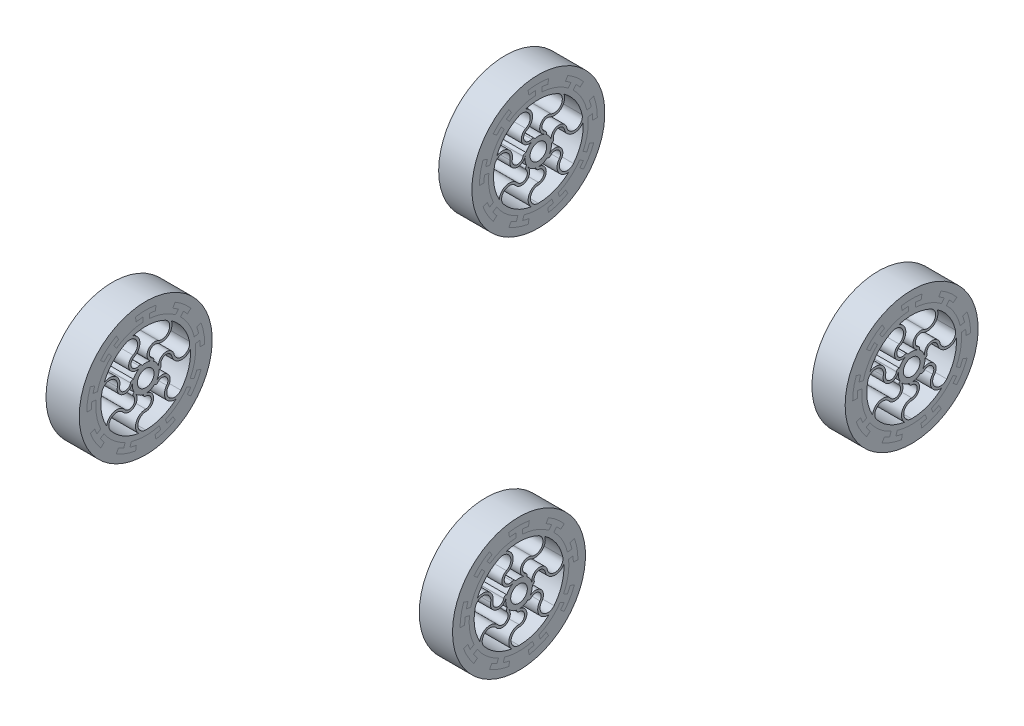
SolidWorks part; units mm, degrees
ref_plane "Front Plane" through (0, 0, 0) normal (0, 0, 1) x (1, 0, 0)
ref_plane "Top Plane" through (0, 0, 0) normal (0, 1, 0) x (1, 0, 0)
ref_plane "Right Plane" through (0, 0, 0) normal (1, 0, 0) x (0, 0, -1)
ref_plane "Plane1" through (64.95, 0, 0) normal (1, 0, 0) x (0, 0, -1)
sketch "Sketch1" plane through (64.95, 0, 0) normal (1, 0, 0) x (0, 0, -1)
  circle A0 centre (0, 0) radius 25.4 construction
  circle A1 centre (0, 0) radius 3.175
  circle A2 centre (0, 0) radius 5.08
  circle A3 centre (0, 0) radius 19.05
  circle A4 centre (0, 0) radius 17.145
  dimension "D1" = 50.8
  dimension "D2" = 38.1
  dimension "D3" = 34.29
  dimension "D4" = 6.35
  dimension "D5" = 10.16
extrude "Boss-Extrude1" add sketch "Sketch1" along normal blind 12.7 contours A3 A4 | A2 A1
sketch "Sketch2" plane through (64.95, 0, 0) normal (1, 0, 0) x (0, 0, -1)
  circle A0 centre (0, 0) radius 5.08
  circle A1 centre (0, 0) radius 17.145
  arc A2 (0, -11.1125) -> (0, -5.08) centre (0, -8.0963) ccw
  arc A3 (0, -11.1125) -> (0, -17.145) centre (0, -14.1288) ccw
  arc A6 (0, -10.2235) -> (-2.7239, -16.9272) centre (0, -14.1288) ccw
  arc A7 (0, -10.2235) -> (0, -5.969) centre (0, -8.0963) ccw
  arc A8 (0, -5.969) -> (-0.8856, -5.0022) centre (0, -5.08) cw
  dimension "D1" = 10.16
  dimension "D2" = 34.29
  dimension "D3" = 0.889
  dimension "D4" = 0
extrude "Boss-Extrude2" add sketch "Sketch2" along normal up to surface (12.7 mm away) contours A8 A7 A6 A1 A3 A2 A0
pattern_circular "CirPattern1" count 7 over 360 about axis through (0, 0, 0) along (1, 0, 0) of "Boss-Extrude2"
sketch "Sketch3" plane through (64.95, 0, 0) normal (1, 0, 0) x (0, 0, -1)
  line L2 (-3.9449, 22.1713) -> (-3.6335, 20.4208)
  line L4 (-1.1102, 20.7118) -> (-1.1102, 19.0176)
  line L6 (3.9449, 22.1713) -> (3.6335, 20.4208)
  line L7 (1.4298, 20.6921) -> (1.4298, 18.9963)
  circle A0 centre (0, 0) radius 19.05 construction
  circle A1 centre (0, 0) radius 19.05
  arc A2 (-3.9449, 22.1713) -> (3.9449, 22.1713) centre (0, 0) cw
  arc A3 (-3.6335, 20.4208) -> (-1.1102, 20.7118) centre (0, 0) cw
  arc A4 (1.4298, 20.6921) -> (3.6335, 20.4208) centre (0, 0) cw
  dimension "D5" = 2.5401
  dimension "D1" = 2.54
  dimension "D2" = 1.778
  dimension "D3" = 2.54
  dimension "D4" = 3.175
extrude "Boss-Extrude3" add sketch "Sketch3" along a picked direction on the side of the normal blind 12.7
pattern_circular "CirPattern2" count 9 over 360 about axis through (0, 0, 0) along (1, 0, 0) of "Boss-Extrude3"
sketch "Sketch5" plane through (64.95, 0, 0) normal (1, 0, 0) x (0, 0, -1)
  line L36 (-1.1102, 20.7118) -> (-1.1102, 19.0176)
  line L37 (-3.9449, 22.1713) -> (-3.6335, 20.4208)
  line L38 (3.6335, 20.4208) -> (3.9449, 22.1713)
  line L39 (1.4298, 18.9963) -> (1.4298, 20.6921)
  line L40 (12.4628, 16.5797) -> (11.3738, 15.282)
  line L41 (11.2294, 19.5199) -> (10.3428, 17.9787)
  line L42 (15.9096, 13.3077) -> (17.2734, 14.4484)
  line L43 (13.3059, 13.6329) -> (14.396, 14.932)
  line L44 (20.2043, 4.6899) -> (18.5359, 4.3957)
  line L45 (21.1494, 7.735) -> (19.4796, 7.1243)
  line L46 (20.7415, -0.0322) -> (22.5195, -0.035)
  line L47 (18.956, 1.8906) -> (20.6261, 2.1851)
  line L48 (18.492, -9.3944) -> (17.0248, -8.5474)
  line L49 (21.1733, -7.6692) -> (19.5016, -7.0637)
  line L50 (15.8682, -13.357) -> (17.2284, -14.502)
  line L51 (15.7363, -10.7364) -> (17.205, -11.5843)
  line L52 (8.1271, -19.083) -> (7.5476, -17.491)
  line L53 (11.29, -19.4849) -> (10.3986, -17.9465)
  line L54 (3.57, -20.432) -> (3.876, -22.1834)
  line L55 (5.1535, -18.3397) -> (5.7335, -19.9333)
  line L56 (-6.0406, -19.8424) -> (-5.4612, -18.2504)
  line L57 (-3.876, -22.1834) -> (-3.57, -20.432)
  line L58 (-10.3986, -17.9465) -> (-11.29, -19.4849)
  line L59 (-7.8407, -17.3616) -> (-8.4207, -18.9552)
  line L60 (-17.3818, -11.3173) -> (-15.9147, -10.4703)
  line L61 (-17.2284, -14.502) -> (-15.8682, -13.357)
  line L62 (-19.5016, -7.0637) -> (-21.1733, -7.6692)
  line L63 (-17.1662, -8.2599) -> (-18.6348, -9.1078)
  line L64 (-20.5899, 2.5032) -> (-18.9215, 2.2091)
  line L65 (-22.5195, -0.035) -> (-20.7415, -0.0322)
  line L66 (-19.4796, 7.1243) -> (-21.1494, 7.735)
  line L67 (-18.4594, 4.7068) -> (-20.1295, 5.0013)
  line L68 (-14.1637, 15.1525) -> (-13.0747, 13.8547)
  line L69 (-17.2734, 14.4484) -> (-15.9096, 13.3077)
  line L70 (-10.3428, 17.9787) -> (-11.2294, 19.5199)
  line L71 (-11.1153, 15.4711) -> (-12.2054, 16.7702)
  line L72 (-1.1102, 20.7118) -> (-1.1102, 19.0176)
  line L73 (-3.9449, 22.1713) -> (-3.6335, 20.4208)
  line L74 (3.6335, 20.4208) -> (3.9449, 22.1713)
  line L75 (1.4298, 18.9963) -> (1.4298, 20.6921)
  line L76 (12.4628, 16.5797) -> (11.3738, 15.282)
  line L77 (11.2294, 19.5199) -> (10.3428, 17.9787)
  line L78 (15.9096, 13.3077) -> (17.2734, 14.4484)
  line L79 (13.3059, 13.6329) -> (14.396, 14.932)
  line L80 (20.2043, 4.6899) -> (18.5359, 4.3957)
  line L81 (21.1494, 7.735) -> (19.4796, 7.1243)
  line L82 (20.7415, -0.0322) -> (22.5195, -0.035)
  line L83 (18.956, 1.8906) -> (20.6261, 2.1851)
  line L84 (18.492, -9.3944) -> (17.0248, -8.5474)
  line L85 (21.1733, -7.6692) -> (19.5016, -7.0637)
  line L86 (15.8682, -13.357) -> (17.2284, -14.502)
  line L87 (15.7363, -10.7364) -> (17.205, -11.5843)
  line L88 (8.1271, -19.083) -> (7.5476, -17.491)
  line L89 (11.29, -19.4849) -> (10.3986, -17.9465)
  line L90 (3.57, -20.432) -> (3.876, -22.1834)
  line L91 (5.1535, -18.3397) -> (5.7335, -19.9333)
  line L92 (-6.0406, -19.8424) -> (-5.4612, -18.2504)
  line L93 (-3.876, -22.1834) -> (-3.57, -20.432)
  line L94 (-10.3986, -17.9465) -> (-11.29, -19.4849)
  line L95 (-7.8407, -17.3616) -> (-8.4207, -18.9552)
  line L96 (-17.3818, -11.3173) -> (-15.9147, -10.4703)
  line L97 (-17.2284, -14.502) -> (-15.8682, -13.357)
  line L98 (-19.5016, -7.0637) -> (-21.1733, -7.6692)
  line L99 (-17.1662, -8.2599) -> (-18.6348, -9.1078)
  line L100 (-20.5899, 2.5032) -> (-18.9215, 2.2091)
  line L101 (-22.5195, -0.035) -> (-20.7415, -0.0322)
  line L102 (-19.4796, 7.1243) -> (-21.1494, 7.735)
  line L103 (-18.4594, 4.7068) -> (-20.1295, 5.0013)
  line L104 (-14.1637, 15.1525) -> (-13.0747, 13.8547)
  line L105 (-17.2734, 14.4484) -> (-15.9096, 13.3077)
  line L106 (-10.3428, 17.9787) -> (-11.2294, 19.5199)
  line L107 (-11.1153, 15.4711) -> (-12.2054, 16.7702)
  circle A0 centre (0, 0) radius 25.4
  arc A37 (-1.1102, 19.0176) -> (-11.1153, 15.4711) centre (0, 0) ccw
  arc A38 (-1.1102, 20.7118) -> (-3.6335, 20.4208) centre (0, 0) ccw
  arc A39 (3.9449, 22.1713) -> (-3.9449, 22.1713) centre (0, 0) ccw
  arc A40 (3.6335, 20.4208) -> (1.4298, 20.6921) centre (0, 0) ccw
  arc A41 (11.3738, 15.282) -> (1.4298, 18.9963) centre (0, 0) ccw
  arc A42 (12.4628, 16.5797) -> (10.3428, 17.9787) centre (0, 0) ccw
  arc A43 (17.2734, 14.4484) -> (11.2294, 19.5199) centre (0, 0) ccw
  arc A44 (15.9096, 13.3077) -> (14.396, 14.932) centre (0, 0) ccw
  arc A45 (18.5359, 4.3957) -> (13.3059, 13.6329) centre (0, 0) ccw
  arc A46 (20.2043, 4.6899) -> (19.4796, 7.1243) centre (0, 0) ccw
  arc A47 (22.5195, -0.035) -> (21.1494, 7.735) centre (0, 0) ccw
  arc A48 (20.7415, -0.0322) -> (20.6261, 2.1851) centre (0, 0) ccw
  arc A49 (17.0248, -8.5474) -> (18.956, 1.8906) centre (0, 0) ccw
  arc A50 (18.492, -9.3944) -> (19.5016, -7.0637) centre (0, 0) ccw
  arc A51 (17.2284, -14.502) -> (21.1733, -7.6692) centre (0, 0) ccw
  arc A52 (15.8682, -13.357) -> (17.205, -11.5843) centre (0, 0) ccw
  arc A53 (7.5476, -17.491) -> (15.7363, -10.7364) centre (0, 0) ccw
  arc A54 (8.1271, -19.083) -> (10.3986, -17.9465) centre (0, 0) ccw
  arc A55 (3.876, -22.1834) -> (11.29, -19.4849) centre (0, 0) ccw
  arc A56 (3.57, -20.432) -> (5.7335, -19.9333) centre (0, 0) ccw
  arc A57 (-5.4612, -18.2504) -> (5.1535, -18.3397) centre (0, 0) ccw
  arc A58 (-6.0406, -19.8424) -> (-3.57, -20.432) centre (0, 0) ccw
  arc A59 (-11.29, -19.4849) -> (-3.876, -22.1834) centre (0, 0) ccw
  arc A60 (-10.3986, -17.9465) -> (-8.4207, -18.9552) centre (0, 0) ccw
  arc A61 (-15.9147, -10.4703) -> (-7.8407, -17.3616) centre (0, 0) ccw
  arc A62 (-17.3818, -11.3173) -> (-15.8682, -13.357) centre (0, 0) ccw
  arc A63 (-21.1733, -7.6692) -> (-17.2284, -14.502) centre (0, 0) ccw
  arc A64 (-19.5016, -7.0637) -> (-18.6348, -9.1078) centre (0, 0) ccw
  arc A65 (-18.9215, 2.2091) -> (-17.1662, -8.2599) centre (0, 0) ccw
  arc A66 (-20.5899, 2.5032) -> (-20.7415, -0.0322) centre (0, 0) ccw
  arc A67 (-21.1494, 7.735) -> (-22.5195, -0.035) centre (0, 0) ccw
  arc A68 (-19.4796, 7.1243) -> (-20.1295, 5.0013) centre (0, 0) ccw
  arc A69 (-13.0747, 13.8547) -> (-18.4594, 4.7068) centre (0, 0) ccw
  arc A70 (-14.1637, 15.1525) -> (-15.9096, 13.3077) centre (0, 0) ccw
  arc A71 (-11.2294, 19.5199) -> (-17.2734, 14.4484) centre (0, 0) ccw
  arc A72 (-10.3428, 17.9787) -> (-12.2054, 16.7702) centre (0, 0) ccw
  arc A73 (-1.1102, 19.0176) -> (-11.1153, 15.4711) centre (0, 0) ccw
  arc A74 (-1.1102, 20.7118) -> (-3.6335, 20.4208) centre (0, 0) ccw
  arc A75 (3.9449, 22.1713) -> (-3.9449, 22.1713) centre (0, 0) ccw
  arc A76 (3.6335, 20.4208) -> (1.4298, 20.6921) centre (0, 0) ccw
  arc A77 (11.3738, 15.282) -> (1.4298, 18.9963) centre (0, 0) ccw
  arc A78 (12.4628, 16.5797) -> (10.3428, 17.9787) centre (0, 0) ccw
  arc A79 (17.2734, 14.4484) -> (11.2294, 19.5199) centre (0, 0) ccw
  arc A80 (15.9096, 13.3077) -> (14.396, 14.932) centre (0, 0) ccw
  arc A81 (18.5359, 4.3957) -> (13.3059, 13.6329) centre (0, 0) ccw
  arc A82 (20.2043, 4.6899) -> (19.4796, 7.1243) centre (0, 0) ccw
  arc A83 (22.5195, -0.035) -> (21.1494, 7.735) centre (0, 0) ccw
  arc A84 (20.7415, -0.0322) -> (20.6261, 2.1851) centre (0, 0) ccw
  arc A85 (17.0248, -8.5474) -> (18.956, 1.8906) centre (0, 0) ccw
  arc A86 (18.492, -9.3944) -> (19.5016, -7.0637) centre (0, 0) ccw
  arc A87 (17.2284, -14.502) -> (21.1733, -7.6692) centre (0, 0) ccw
  arc A88 (15.8682, -13.357) -> (17.205, -11.5843) centre (0, 0) ccw
  arc A89 (7.5476, -17.491) -> (15.7363, -10.7364) centre (0, 0) ccw
  arc A90 (8.1271, -19.083) -> (10.3986, -17.9465) centre (0, 0) ccw
  arc A91 (3.876, -22.1834) -> (11.29, -19.4849) centre (0, 0) ccw
  arc A92 (3.57, -20.432) -> (5.7335, -19.9333) centre (0, 0) ccw
  arc A93 (-5.4612, -18.2504) -> (5.1535, -18.3397) centre (0, 0) ccw
  arc A94 (-6.0406, -19.8424) -> (-3.57, -20.432) centre (0, 0) ccw
  arc A95 (-11.29, -19.4849) -> (-3.876, -22.1834) centre (0, 0) ccw
  arc A96 (-10.3986, -17.9465) -> (-8.4207, -18.9552) centre (0, 0) ccw
  arc A97 (-15.9147, -10.4703) -> (-7.8407, -17.3616) centre (0, 0) ccw
  arc A98 (-17.3818, -11.3173) -> (-15.8682, -13.357) centre (0, 0) ccw
  arc A99 (-21.1733, -7.6692) -> (-17.2284, -14.502) centre (0, 0) ccw
  arc A100 (-19.5016, -7.0637) -> (-18.6348, -9.1078) centre (0, 0) ccw
  arc A101 (-18.9215, 2.2091) -> (-17.1662, -8.2599) centre (0, 0) ccw
  arc A102 (-20.5899, 2.5032) -> (-20.7415, -0.0322) centre (0, 0) ccw
  arc A103 (-21.1494, 7.735) -> (-22.5195, -0.035) centre (0, 0) ccw
  arc A104 (-19.4796, 7.1243) -> (-20.1295, 5.0013) centre (0, 0) ccw
  arc A105 (-13.0747, 13.8547) -> (-18.4594, 4.7068) centre (0, 0) ccw
  arc A106 (-14.1637, 15.1525) -> (-15.9096, 13.3077) centre (0, 0) ccw
  arc A107 (-11.2294, 19.5199) -> (-17.2734, 14.4484) centre (0, 0) ccw
  arc A108 (-10.3428, 17.9787) -> (-12.2054, 16.7702) centre (0, 0) ccw
  dimension "D1" = 50.8
  dimension "D2" = 0
extrude "Boss-Extrude4" add sketch "Sketch5" along normal up to surface (12.7 mm away) separate body up to face at (77.65, -8.4949, 4.395)
sketch "Sketch4" plane through (0, 0, 0) normal (1, 0, 0) x (0, 0, -1)
  line L0 (0, 0) -> (-150, 0) construction
pattern_linear "LPattern1" count 2 spacing 150 along (0, 0, 1) of bodies 111 107
mirror "Mirror1" about plane through (0, 0, 0) normal (1, 0, 0) of bodies 107 108 112 111
